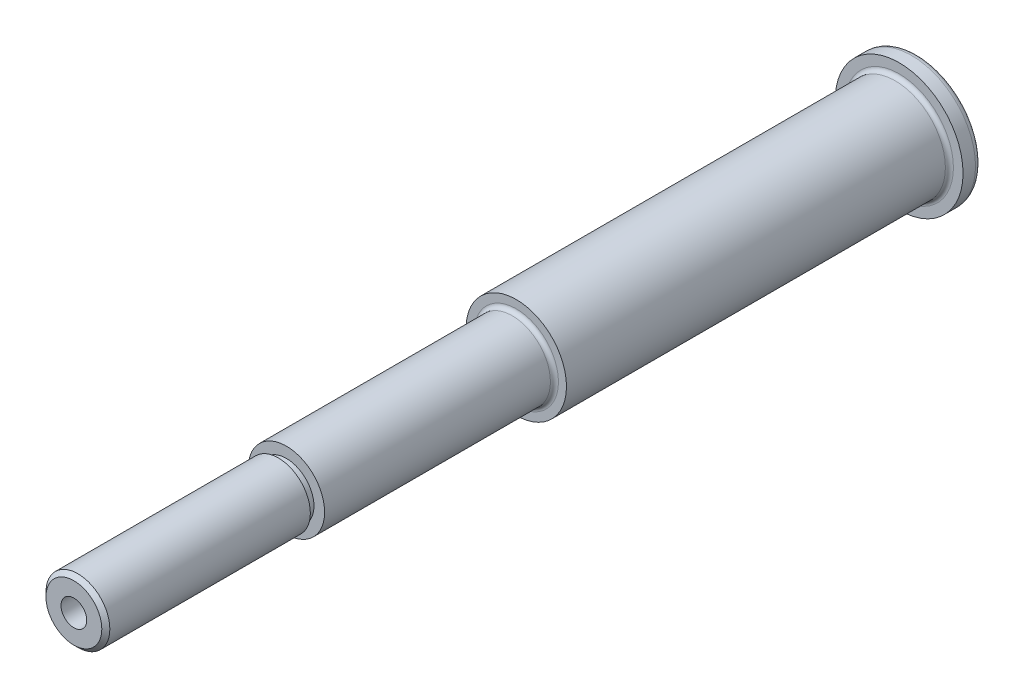
SolidWorks part; units mm, degrees
ref_plane "Front" through (0, 0, 0) normal (0, 0, 1) x (1, 0, 0)
ref_plane "Top" through (0, 0, 0) normal (0, 1, 0) x (1, 0, 0)
ref_plane "Right" through (0, 0, 0) normal (1, 0, 0) x (0, 0, -1)
sketch "Sketch2" plane through (0, 0, 0) normal (1, 0, 0) x (0, 0, -1)
  line L0 (0, 0) -> (8.2733, 0) construction
  line L1 (0, 0) -> (0, 14.4)
  line L2 (-1.5, 15.9) -> (-4.6, 15.9)
  line L3 (-4.6, 15.9) -> (-4.6, 13.5)
  line L4 (-5.6, 12.5) -> (-99.9, 12.5)
  line L5 (-99.9, 12.5) -> (-99.9, 10.5)
  line L6 (-100.9, 9.5) -> (-157.1, 9.5)
  line L7 (-157.1, 9.5) -> (-157.1, 6.85)
  line L8 (-157.1, 6.85) -> (-159.1, 6.85)
  line L9 (-159.1, 6.85) -> (-159.1, 7.95)
  line L10 (-159.1, 7.95) -> (-209, 7.95)
  line L11 (-210, 6.95) -> (-210, 0)
  line L12 (-210, 0) -> (0, 0)
  line L13 (-209, 7.95) -> (-210, 6.95)
  arc A0 (-100.9, 9.5) -> (-99.9, 10.5) centre (-100.9, 10.5) ccw
  arc A1 (-1.5, 15.9) -> (0, 14.4) centre (-1.5, 14.4) cw
  arc A2 (-5.6, 12.5) -> (-4.6, 13.5) centre (-5.6, 13.5) ccw
  point P12 (-210, 7.95)
  point P20 (0, 15.9)
  point P23 (-4.6, 12.5)
  dimension "D2" = 1
  dimension "D14" = 1.5
  dimension "D1" = 31.8
  dimension "D3" = 25
  dimension "D4" = 4.6
  dimension "D5" = 19
  dimension "D6" = 210
  dimension "D7" = 95.3
  dimension "D8" = 57.2
  dimension "D9" = 13.7
  dimension "D10" = 2
  dimension "D11" = 15.9
  dimension "D12" = 1
  dimension "D13" = 45
revolve "Base-Revolve" add sketch "Sketch2" angle 360 about L0
sketch "Sketch3" plane through (0, 0, 210) normal (0, 0, 1) x (1, 0, 0)
  circle A0 centre (0, 0) radius 3.2
  dimension "D1" = 6.4
extrude "Cut-Extrude1" cut sketch "Sketch3" against normal blind 35
